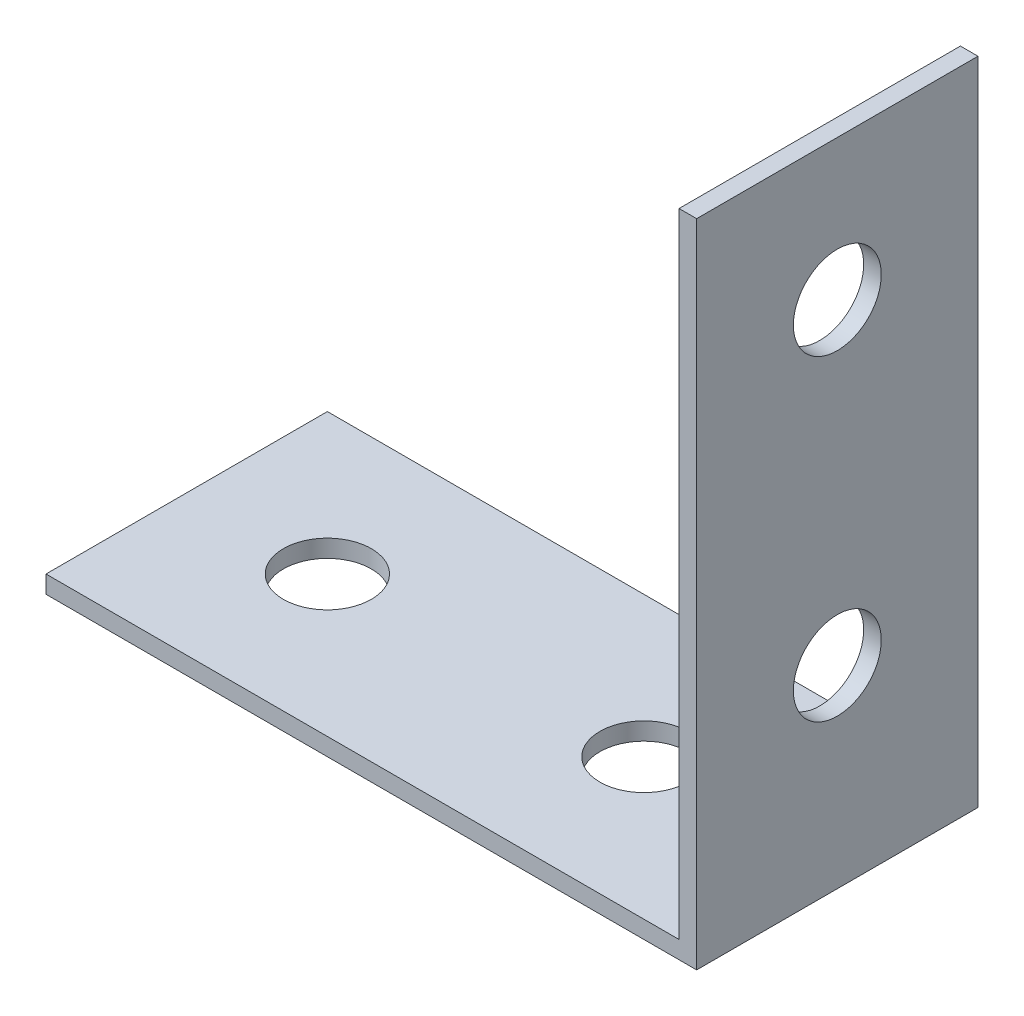
SolidWorks part; units mm, degrees
ref_plane "前基準面" through (0, 0, 0) normal (0, 0, 1) x (1, 0, 0)
ref_plane "上基準面" through (0, 0, 0) normal (0, 1, 0) x (1, 0, 0)
ref_plane "右基準面" through (0, 0, 0) normal (1, 0, 0) x (0, 0, -1)
sketch "草圖1" plane through (0, 0, 0) normal (0, 1, 0) x (1, 0, 0)
  line L1 (-18, 8) -> (18, 8)
  line L2 (-18, 8) -> (-18, -8)
  line L3 (-18, -8) -> (18, -8)
  line L4 (18, 8) -> (18, -8)
  line L5 (-18, 8) -> (18, -8) construction
  line L6 (-18, -8) -> (18, 8) construction
  point P0 (0, 0)
  dimension "D1" = 36
  dimension "D2" = 16
extrude "填料-伸長1" add sketch "草圖1" along normal blind 1
sketch "草圖2" plane through (18, 0, 0) normal (1, 0, 0) x (0, 0, -1)
  line L0 (8, 1) -> (8, 0) construction
  line L1 (-8, 0) -> (8, 0)
  line L2 (-8, 0) -> (-8, 37)
  line L3 (-8, 37) -> (8, 37)
  line L4 (8, 0) -> (8, 37)
  dimension "D1" = 37
extrude "填料-伸長2" add sketch "草圖2" along normal blind 1
sketch "草圖3" plane through (0, 1, 0) normal (0, 1, 0) x (1, 0, 0)
  line L0 (-18, 8) -> (-18, -8) construction
  circle A0 centre (-10, 0) radius 2.5
  circle A1 centre (8, 0) radius 2.5
  dimension "D1" = 5
  dimension "D2" = 8
  dimension "D3" = 18
extrude "除料-伸長1" cut sketch "草圖3" against normal up to next
sketch "草圖4" plane through (18, 0, 0) normal (-1, 0, 0) x (0, 0, 1)
  line L0 (-8, 37) -> (8, 37) construction
  circle A0 centre (0, 29) radius 2.5
  circle A1 centre (0, 11) radius 2.5
  dimension "D1" = 5
  dimension "D2" = 8
  dimension "D3" = 18
extrude "除料-伸長2" cut sketch "草圖4" against normal up to next
